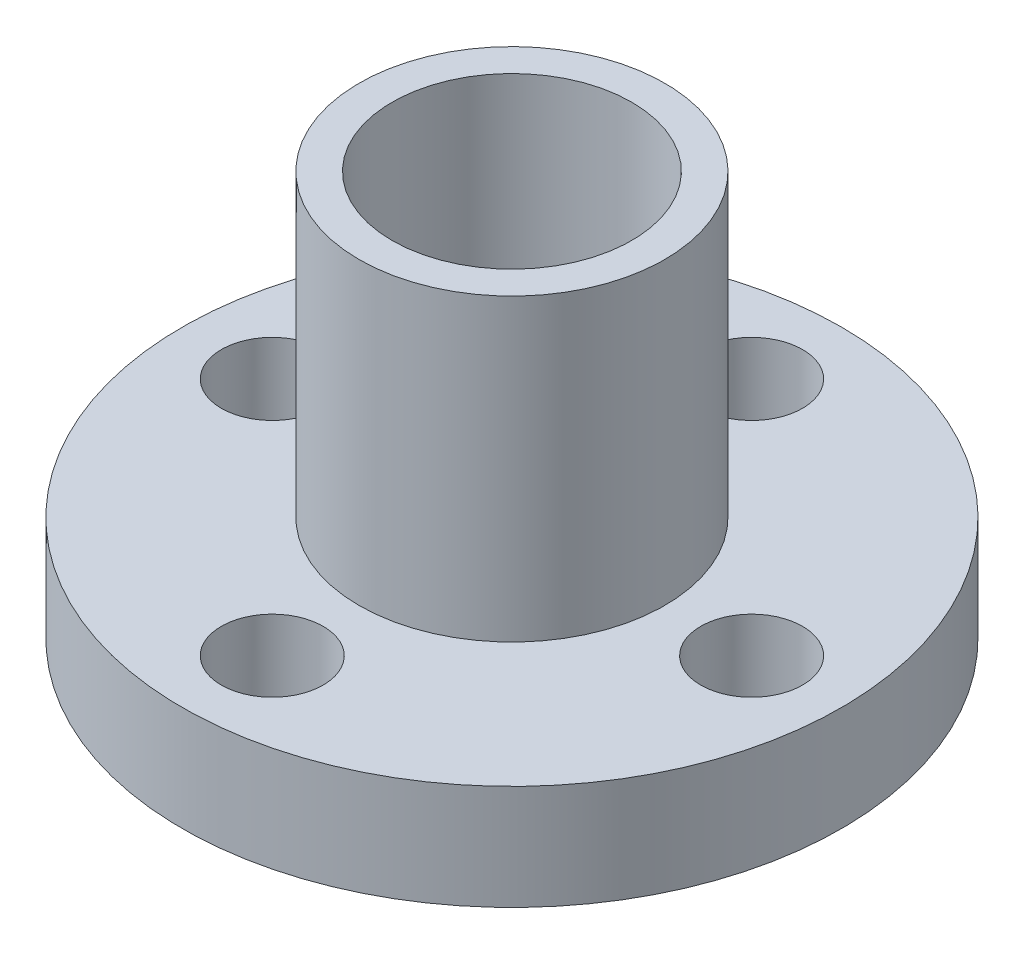
SolidWorks part; units mm, degrees
material "Brass"
ref_plane "Front Plane" through (0, 0, 0) normal (0, 0, 1) x (1, 0, 0)
ref_plane "Top Plane" through (0, 0, 0) normal (0, 1, 0) x (1, 0, 0)
ref_plane "Right Plane" through (0, 0, 0) normal (1, 0, 0) x (0, 0, -1)
sketch "Sketch1" plane through (0, 0, 0) normal (0, 1, 0) x (1, 0, 0)
  circle A0 centre (0, 0) radius 4
  circle A1 centre (0, 0) radius 5.1
  dimension "D1" = 8
  dimension "D2" = 10.2
extrude "Boss-Extrude1" add sketch "Sketch1" against normal blind 10 contours A1 A0
sketch "Sketch2" plane through (0, -10, 0) normal (0, -1, 0) x (1, 0, 0)
  circle A0 centre (0, 0) radius 4 construction
  circle A1 centre (0, 0) radius 4
  circle A2 centre (0, 0) radius 11
  dimension "D1" = 22
extrude "Boss-Extrude2" add sketch "Sketch2" along normal blind 3.5
sketch "Sketch3" plane through (0, -13.5, 0) normal (0, -1, 0) x (1, 0, 0)
  circle A0 centre (0, 0) radius 4 construction
  circle A1 centre (0, 0) radius 4
  circle A2 centre (0, 0) radius 5.1 construction
  circle A3 centre (0, 0) radius 5.1
extrude "Boss-Extrude3" add sketch "Sketch3" along normal blind 1.5
sketch "Sketch4" plane through (0, -10, 0) normal (0, 1, 0) x (1, 0, 0)
  circle A0 centre (0, 0) radius 8 construction
  point P3 (0, 8)
  point P4 (0, -8)
  point P5 (-8, 0)
  point P6 (8, 0)
  dimension "D1" = 16
hole_wizard "M3 Clearance Hole1" positions "Sketch4" profile "Sketch5" hole size "M3" standard "ANSI Metric" end condition through all
sketch "Sketch5" plane through (8, -10, 0) normal (1, 0, 0) x (0, 0, 1)
  line L0 (0, 0) -> (0, 5)
  line L1 (0, 5) -> (1.7, 5)
  line L2 (1.7, 5) -> (1.7, 0)
  line L5 (1.7, 0) -> (0, 0)
  line L11 (0, -6.35) -> (0, 107.95) construction
  dimension "Thru Hole Dia." = 3.4
  dimension "Thru Hole Depth" = 5
